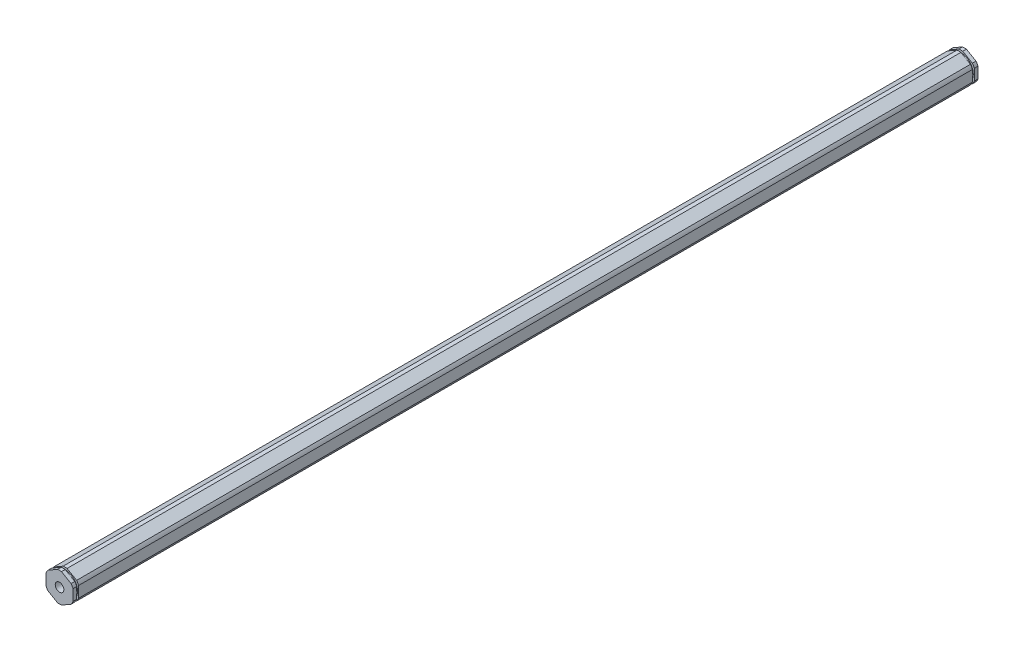
SolidWorks part; units mm, degrees
ref_plane "Front Plane" through (0, 0, 0) normal (0, 0, 1) x (1, 0, 0)
ref_plane "Top Plane" through (0, 0, 0) normal (0, 1, 0) x (1, 0, 0)
ref_plane "Right Plane" through (0, 0, 0) normal (1, 0, 0) x (0, 0, -1)
sketch "Sketch1" plane through (0, 0, 0) normal (0, 0, 1) x (1, 0, 0)
  line L1 (0, 7.3323) -> (-6.35, 3.6662)
  line L2 (-6.35, 3.6662) -> (-6.35, -3.6662)
  line L3 (-6.35, -3.6662) -> (0, -7.3323)
  line L4 (0, -7.3323) -> (6.35, -3.6662)
  line L5 (6.35, -3.6662) -> (6.35, 3.6662)
  line L6 (6.35, 3.6662) -> (0, 7.3323)
  circle A0 centre (0, 0) radius 6.35 construction
  circle A1 centre (0, 0) radius 6.858
  dimension "D1" = 12.7
  dimension "D2" = 13.716
extrude "Boss-Extrude1" add sketch "Sketch1" along normal mid plane 424.4467 contours L5 A1 L6 L1 L2 L3 L4
hole_wizard "#10-32 Tapped Hole1" positions "3DSketch1" profile "Sketch2" tap size "#10-32" standard "ANSI Inch"
sketch3d "3DSketch1"
  line L0 (0, 0, 212.2233) -> (0, 0, -212.2233) construction
  line L1 (0, 0, 212.2233) -> (0, 0, -212.2233) construction
  point P0 (0, 0, 212.2233)
  point P4 (0, 0, -212.2233)
sketch "Sketch2" plane through (0, 0, 212.2233) normal (1, 0, 0) x (0, -1, 0)
  line L0 (0, 0) -> (0, 17.5608)
  line L1 (0, 17.5608) -> (2.0193, 16.3474)
  line L2 (2.0193, 16.3474) -> (2.0193, 0)
  line L5 (2.0193, 0) -> (0, 0)
  line L10 (0, 17.5608) -> (-2.0193, 16.3474) construction
  line L11 (0, -6.35) -> (0, 107.95) construction
  dimension "Tap Drill Dia." = 4.0386
  dimension "Tap Drill Depth" = 16.3474
  dimension "Drill Angle" = 118
cosmetic thread "Hole Thread1" parameters "D1"=13.97, "D2"=4.826
cosmetic thread "Hole Thread2" parameters "D1"=13.97, "D2"=4.826
sketch "Sketch5" plane through (0, 0, 0) normal (1, 0, 0) x (0, 0, -1)
  line L0 (212.2233, 6.858) -> (-212.2233, 6.858) construction
  line L1 (-210.5088, 6.858) -> (-209.6198, 6.858)
  line L2 (-210.5088, 6.858) -> (-210.5088, 5.8547)
  line L3 (-210.5088, 5.8547) -> (-209.6198, 5.8547)
  line L4 (-209.6198, 6.858) -> (-209.6198, 5.8547)
  line L5 (-165.0472, 0) -> (-158.8423, 0) construction
  dimension "D1" = 5.8547
  dimension "D2" = 0.889
  dimension "D3" = 1.7145
revolve "Cut-Revolve1" cut sketch "Sketch5" angle 360 about L5
mirror "Mirror1" about plane through (0, 0, 0) normal (0, 0, 1) of "Cut-Revolve1"
